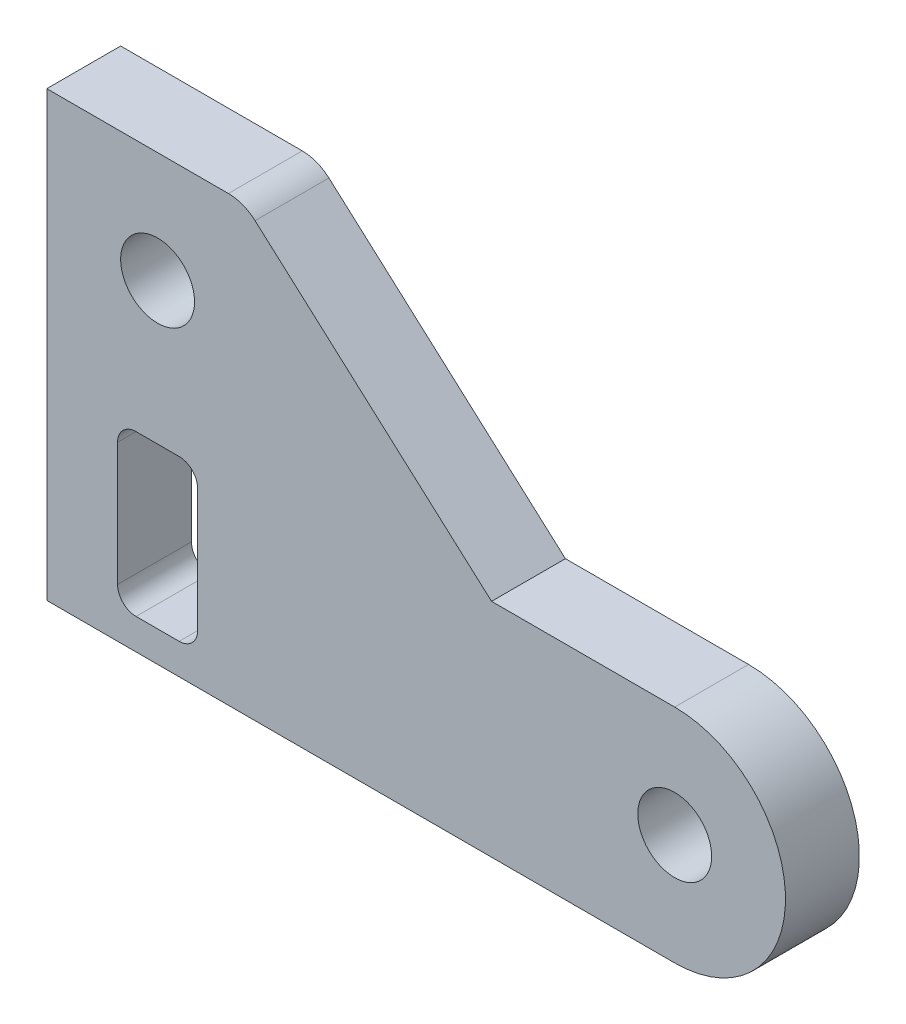
SolidWorks part; units mm, degrees
ref_plane "Alzado" through (0, 0, 0) normal (0, 0, 1) x (1, 0, 0)
ref_plane "Planta" through (0, 0, 0) normal (0, 1, 0) x (1, 0, 0)
ref_plane "Vista lateral" through (0, 0, 0) normal (1, 0, 0) x (0, 0, -1)
sketch "Model" plane through (0, 0, 0) normal (0, 0, 1) x (1, 0, 0)
  line L0 (179.2229, 265.8965) -> (180.9729, 265.8965)
  line L1 (181.7229, 266.6465) -> (181.7229, 271.6465)
  line L2 (180.9729, 272.3965) -> (179.2229, 272.3965)
  line L3 (178.4729, 271.6465) -> (178.4729, 266.6465)
  line L4 (182.9729, 282.6465) -> (175.5979, 282.6465)
  line L5 (175.5979, 282.6465) -> (175.5979, 264.6465)
  line L6 (201.0979, 264.6465) -> (175.5979, 264.6465)
  line L7 (193.6604, 273.6465) -> (201.0979, 273.6465)
  line L8 (184.0559, 282.233) -> (193.6604, 273.6465)
  circle A0 centre (201.0979, 269.1465) radius 1.5
  arc A1 (178.4729, 266.6465) -> (179.2229, 265.8965) centre (179.2229, 266.6465) ccw
  arc A2 (180.9729, 265.8965) -> (181.7229, 266.6465) centre (180.9729, 266.6465) ccw
  arc A3 (181.7229, 271.6465) -> (180.9729, 272.3965) centre (180.9729, 271.6465) ccw
  arc A4 (179.2229, 272.3965) -> (178.4729, 271.6465) centre (179.2229, 271.6465) ccw
  arc A5 (201.0979, 264.6465) -> (201.0979, 273.6465) centre (201.0979, 269.1465) ccw
  arc A6 (184.0559, 282.233) -> (182.9729, 282.6465) centre (182.9729, 281.0215) ccw
  circle A7 centre (180.0979, 278.146) radius 1.5
extrude "Saliente-Extruir1" add sketch "Model" along normal blind 3
